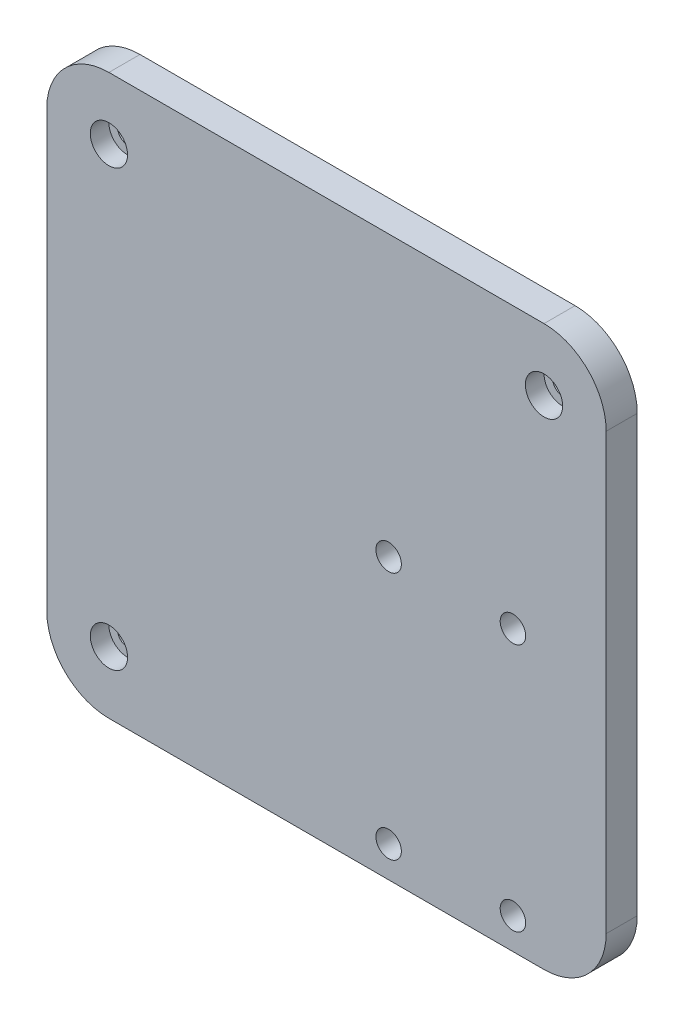
SolidWorks part; units mm, degrees
ref_plane "正面" through (0, 0, 0) normal (0, 0, 1) x (1, 0, 0)
ref_plane "平面" through (0, 0, 0) normal (0, 1, 0) x (1, 0, 0)
ref_plane "右側面" through (0, 0, 0) normal (1, 0, 0) x (0, 0, -1)
sketch "ｽｹｯﾁ1" plane through (0, 0, 0) normal (0, 0, 1) x (1, 0, 0)
  line L1 (35, -35) -> (-35, -35) construction
  line L2 (35, -35) -> (35, 35) construction
  line L3 (35, 35) -> (-35, 35) construction
  line L4 (-35, -35) -> (-35, 35) construction
  line L5 (35, -35) -> (-35, 35) construction
  line L6 (35, 35) -> (-35, -35) construction
  line L7 (-35, 45) -> (35, 45)
  line L8 (-45, 35) -> (-45, -35)
  line L9 (-35, -45) -> (35, -45)
  line L10 (45, 35) -> (45, -35)
  line L11 (-45, 45) -> (45, -45) construction
  line L12 (-45, -45) -> (45, 45) construction
  circle A0 centre (-35, -35) radius 1.6
  circle A1 centre (-35, 35) radius 1.6
  circle A2 centre (35, 35) radius 1.6
  arc A3 (35, 45) -> (45, 35) centre (35, 35) cw
  arc A4 (-35, 45) -> (-45, 35) centre (-35, 35) ccw
  arc A5 (-45, -35) -> (-35, -45) centre (-35, -35) ccw
  arc A6 (35, -45) -> (45, -35) centre (35, -35) ccw
  point P0 (0, 0)
  point P9 (0, 0)
  dimension "D1" = 70
  dimension "D2" = 3.2
  dimension "D4" = 10
  dimension "D3" = 10
extrude "ﾎﾞｽ - 押し出し1" add sketch "ｽｹｯﾁ1" along normal blind 5
sketch "ｽｹｯﾁ2" plane through (0, 0, 5) normal (0, 0, 1) x (1, 0, 0)
  circle A0 centre (-35, 35) radius 3
  circle A1 centre (35, 35) radius 3
  circle A2 centre (-35, -35) radius 3
  dimension "D1" = 6
extrude "ｶｯﾄ - 押し出し1" cut sketch "ｽｹｯﾁ2" against normal blind 3
sketch "ｽｹｯﾁ3" plane through (0, 0, 5) normal (0, 0, 1) x (1, 0, 0)
  line L0 (35, -45) -> (45, -45) construction
  line L1 (45, -45) -> (45, -35) construction
  line L2 (-5, -45) -> (45, 5) construction
  line L3 (45, -45) -> (-5, -45) construction
  line L4 (45, -45) -> (45, 5) construction
  line L5 (45, 5) -> (-5, 5) construction
  line L6 (-5, -45) -> (-5, 5) construction
  line L7 (-5, 5) -> (45, -45) construction
  line L9 (10, 0) -> (30, 0) construction
  line L10 (10, 0) -> (10, -40) construction
  line L11 (10, -40) -> (30, -40) construction
  line L12 (30, 0) -> (30, -40) construction
  line L13 (10, 0) -> (30, -40) construction
  line L14 (10, -40) -> (30, 0) construction
  circle A0 centre (30, 0) radius 2.05
  circle A1 centre (10, 0) radius 2.05
  circle A2 centre (10, -40) radius 2.05
  circle A3 centre (30, -40) radius 2.05
  point P9 (20, -20)
  point P18 (0, 0)
  point P19 (19.8293, -18.2979)
  point P20 (0, 0)
  point P21 (0, 0)
  dimension "D4" = 4.1
  dimension "D1" = 50
  dimension "D2" = 20
  dimension "D3" = 40
extrude "ｶｯﾄ - 押し出し2" cut sketch "ｽｹｯﾁ3" against normal through all
